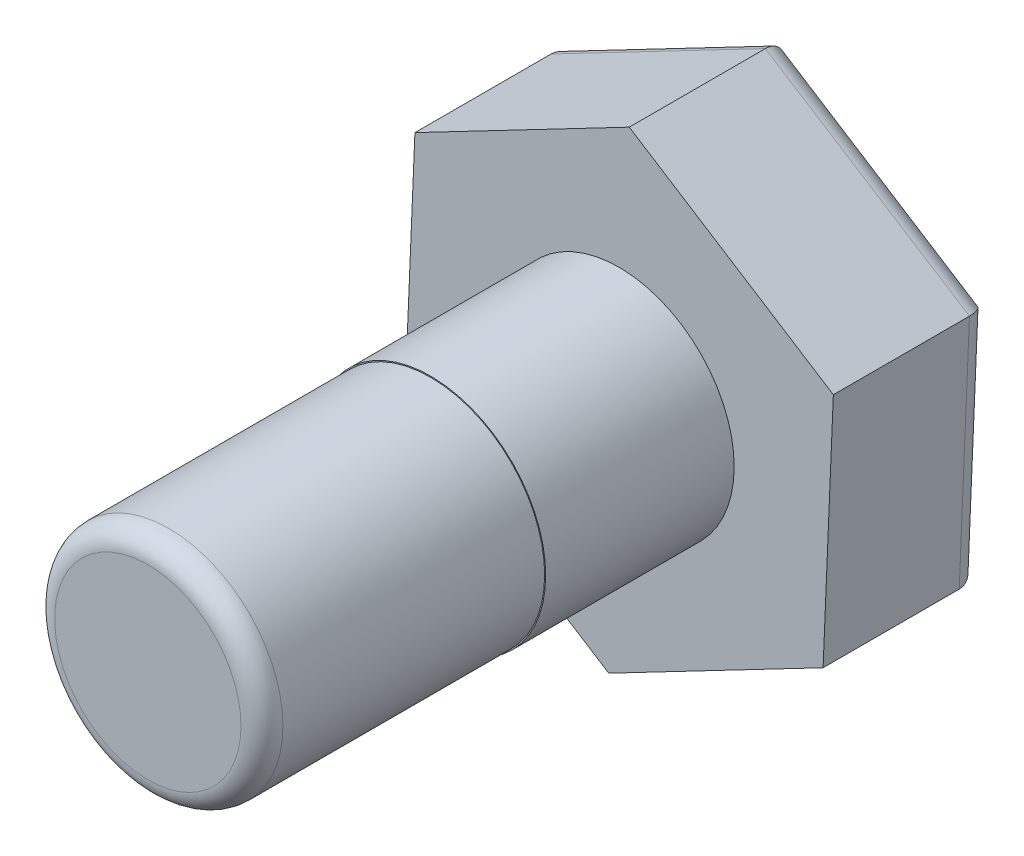
SolidWorks part; units mm, degrees
ref_plane "前视" through (0, 0, 0) normal (0, 0, 1) x (1, 0, 0)
ref_plane "上视" through (0, 0, 0) normal (0, 1, 0) x (1, 0, 0)
ref_plane "右视" through (0, 0, 0) normal (1, 0, 0) x (0, 0, -1)
sketch "草图1" plane through (0, 0, 0) normal (0, 0, 1) x (1, 0, 0)
  line L1 (20.4724, 10.6871) -> (0.9809, 23.0732)
  line L2 (0.9809, 23.0732) -> (-19.4915, 12.3861)
  line L3 (-19.4915, 12.3861) -> (-20.4724, -10.6871)
  line L4 (-20.4724, -10.6871) -> (-0.9809, -23.0732)
  line L5 (-0.9809, -23.0732) -> (19.4915, -12.3861)
  line L6 (19.4915, -12.3861) -> (20.4724, 10.6871)
  circle A0 centre (0, 0) radius 20 construction
  dimension "D1" = 40
extrude "基体-拉伸" add sketch "草图1" along normal blind 15
sketch "草图2" plane through (0, 0, 15) normal (0, 0, 1) x (1, 0, 0)
  circle A0 centre (0, 0) radius 11
  dimension "D1" = 22
extrude "凸台-拉伸1" add sketch "草图2" along normal blind 18
fillet "圆角3" radius 2 6 edges at (9.2553, -17.7296, 0) (-10.7266, -16.8801, 0) (-19.982, 0.8495, 0) (-9.2553, 17.7296, 0) (10.7266, 16.8801, 0) (19.982, -0.8495, 0)
sketch "草图3" plane through (0, 0, 33) normal (0, 0, 1) x (1, 0, 0)
  circle A0 centre (0, 0) radius 10.9
extrude "拉伸1" add sketch "草图3" along normal blind 27
fillet "圆角4" radius 2 1 edges at (10.9, 0, 60)
